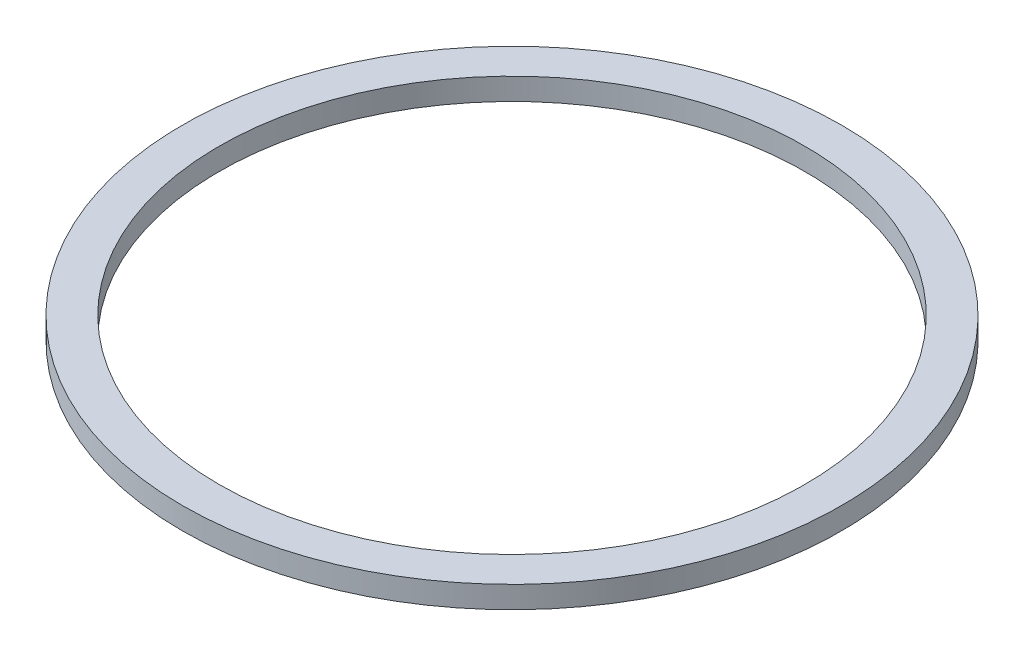
SolidWorks part; units mm, degrees
ref_plane "Front Plane" through (0, 0, 0) normal (0, 0, 1) x (1, 0, 0)
ref_plane "Top Plane" through (0, 0, 0) normal (0, 1, 0) x (1, 0, 0)
ref_plane "Right Plane" through (0, 0, 0) normal (1, 0, 0) x (0, 0, -1)
sketch "Sketch2" plane through (0, 0, 0) normal (0, 1, 0) x (1, 0, 0)
  circle A0 centre (0, 0) radius 33.36
  circle A1 centre (0, 0) radius 37.53
extrude "Boss-Extrude1" add sketch "Sketch2" along normal blind 2.5 contours A1 | A0
